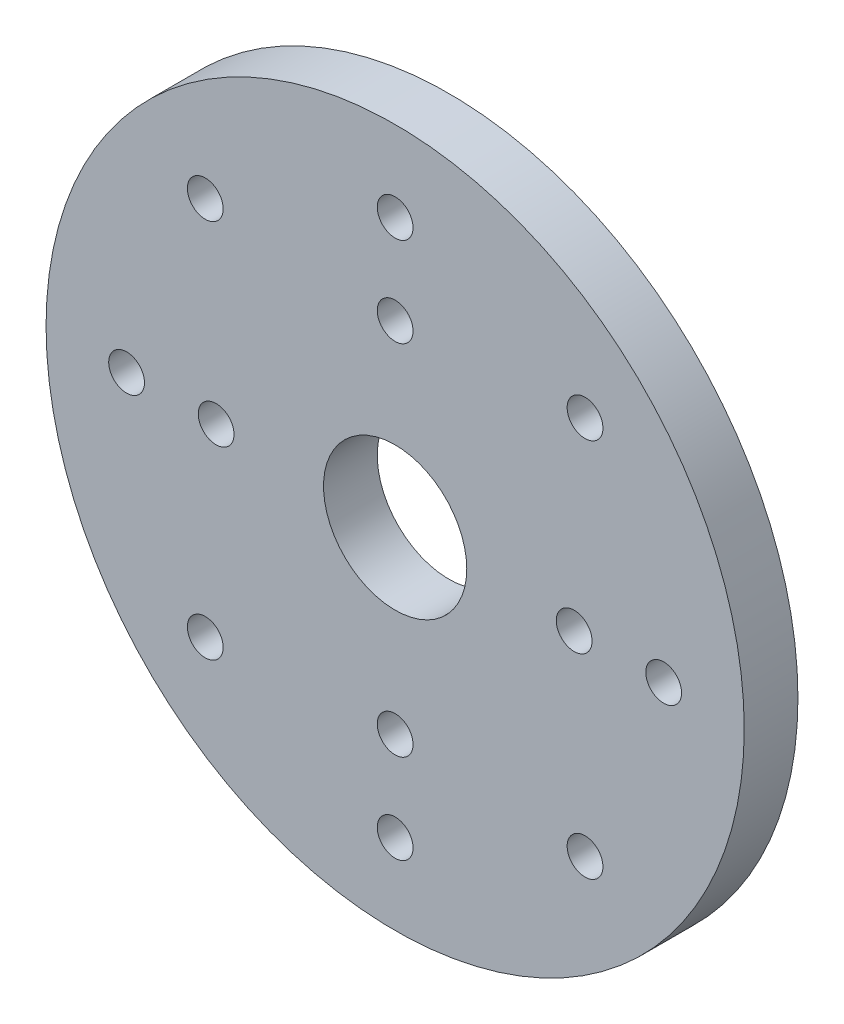
SolidWorks part; units mm, degrees
ref_plane "Alzado" through (0, 0, 0) normal (0, 0, 1) x (1, 0, 0)
ref_plane "Planta" through (0, 0, 0) normal (0, 1, 0) x (1, 0, 0)
ref_plane "Vista lateral" through (0, 0, 0) normal (1, 0, 0) x (0, 0, -1)
sketch "Croquis1" plane through (0, 0, 0) normal (0, 0, 1) x (1, 0, 0)
  circle A0 centre (0, 0) radius 19.5
  dimension "D1" = 39
extrude "Saliente-Extruir1" add sketch "Croquis1" along normal blind 3
sketch "Croquis2" plane through (0, 0, 3) normal (0, 0, 1) x (1, 0, 0)
  line L0 (0, 0) -> (0, 19.5) construction
  circle A0 centre (0, 0) radius 19.5 construction
  circle A1 centre (0, 10) radius 1
  circle A2 centre (10, 0) radius 1
  circle A3 centre (0, -10) radius 1
  circle A4 centre (-10, 0) radius 1
  circle A5 centre (0, 15) radius 1
  circle A6 centre (10.6066, 10.6066) radius 1
  circle A7 centre (15, 0) radius 1
  circle A8 centre (10.6066, -10.6066) radius 1
  circle A9 centre (0, -15) radius 1
  circle A10 centre (-10.6066, -10.6066) radius 1
  circle A11 centre (-15, 0) radius 1
  circle A12 centre (-10.6066, 10.6066) radius 1
  point P17 (0, 0)
  point P33 (0, 0)
  dimension "D1" = 2
  dimension "D2" = 10
  dimension "D4" = 15
  dimension "D3" = 4
  dimension "D5" = 8
extrude "Cortar-Extruir1" cut sketch "Croquis2" against normal up to surface (3 mm away) up to face at (19.5, 0, 0)
sketch "Croquis3" plane through (0, 0, 3) normal (0, 0, 1) x (1, 0, 0)
  circle A0 centre (0, 0) radius 4
  dimension "D1" = 8
extrude "Cortar-Extruir2" cut sketch "Croquis3" against normal up to surface (3 mm away) up to face at (1, -15, 0)
